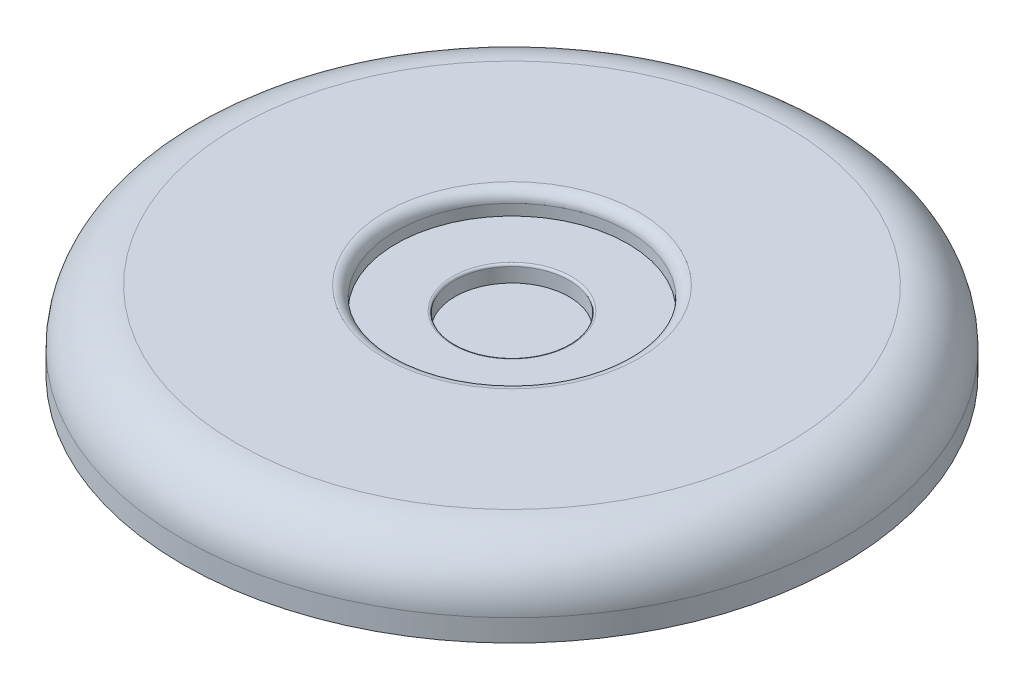
SolidWorks part; units mm, degrees
ref_plane "Front Plane" through (0, 0, 0) normal (0, 0, 1) x (1, 0, 0)
ref_plane "Top Plane" through (0, 0, 0) normal (0, 1, 0) x (1, 0, 0)
ref_plane "Right Plane" through (0, 0, 0) normal (1, 0, 0) x (0, 0, -1)
sketch "Sketch1" plane through (0, 0, 0) normal (1, 0, 0) x (0, 0, -1)
  line L2 (0, 0) -> (-30, 0)
  line L3 (-10.55, 7) -> (-10.55, 5)
  line L4 (-10.55, 5) -> (0, 5)
  line L5 (0, 5) -> (0, 0)
  line L6 (-10.55, 7) -> (-20.1025, 7)
  line L7 (-30, 0) -> (-30, 7)
  line L8 (-30, 7) -> (-20.1025, 7)
  dimension "D3" = 10.55
  dimension "D1" = 2
  dimension "D2" = 5
  dimension "D4" = 30
revolve "Revolve1" add sketch "Sketch1" angle 360 about L5
fillet "Fillet1" radius 1 1 edges at (0, 7, 10.55)
sketch "Sketch2" plane through (0, 5, 0) normal (0, 1, 0) x (1, 0, 0)
  circle A0 centre (0, 0) radius 5.2
  dimension "D1" = 10.4
extrude "Cut-Extrude1" cut sketch "Sketch2" against normal blind 1.5
fillet "Fillet2" radius 0.2 1 edges at (0, 5, 5.2)
fillet "Fillet3" radius 5 1 edges at (0, 7, 30)
ref_plane "Plane1" through (0, 0, 0) normal (0, -1, 0) x (-1, 0, 0)
sketch "Sketch4" plane through (0, 0, 0) normal (0, -1, 0) x (1, 0, 0)
  text T0 "1"
  text T1 "2"
  text T2 "3"
  text T3 "4"
extrude "Cut-Extrude2" cut sketch "Sketch4" against normal blind 1
sketch "Sketch5" plane through (0, 0, 0) normal (0, -1, 0) x (1, 0, 0)
  line L0 (0, -30) -> (0, 30)
  line L1 (-30, 0) -> (30, 0)
  circle A0 centre (0, 0) radius 30 construction
